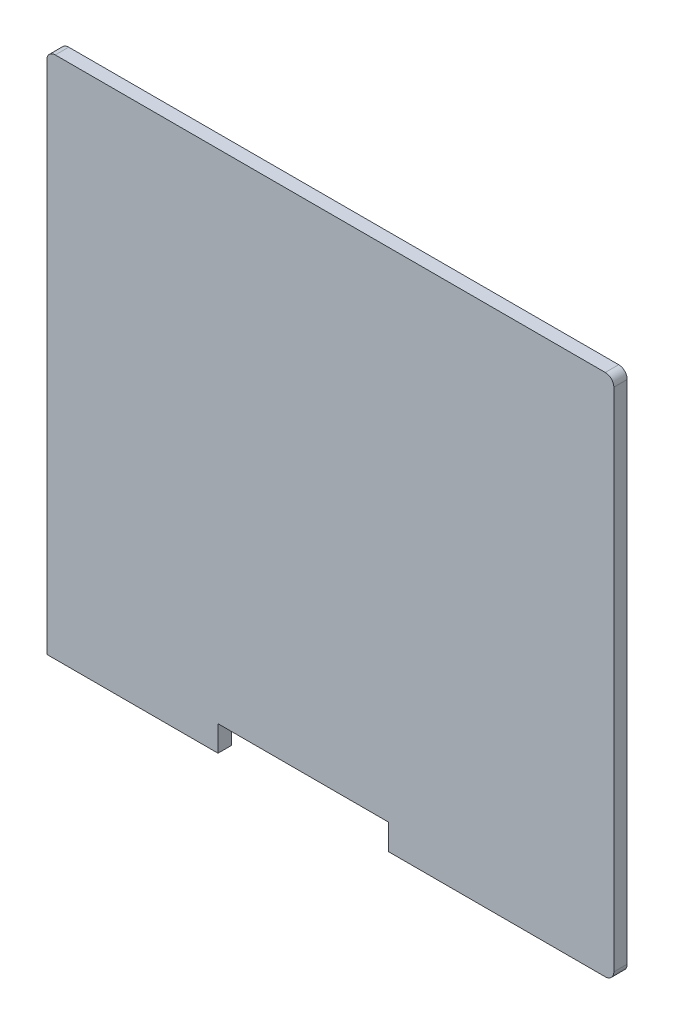
SolidWorks part; units mm, degrees
ref_plane "Front Plane" through (0, 0, 0) normal (0, 0, 1) x (1, 0, 0)
ref_plane "Top Plane" through (0, 0, 0) normal (0, 1, 0) x (1, 0, 0)
ref_plane "Right Plane" through (0, 0, 0) normal (1, 0, 0) x (0, 0, -1)
sketch "BPR2 PCB Outline" plane through (0, 0, 0) normal (0, 0, 1) x (1, 0, 0)
  line L0 (75.643, 7.3176) -> (75.643, 10.3176)
  line L1 (56.571, 68.6726) -> (121.041, 68.6726)
  line L2 (55.571, 67.6726) -> (55.571, 7.3176)
  line L3 (55.571, 7.3176) -> (75.643, 7.3176)
  line L4 (122.041, 67.6726) -> (122.041, 8.3176)
  line L5 (75.643, 10.3176) -> (95.643, 10.3176)
  line L6 (95.643, 10.3176) -> (95.643, 7.3176)
  line L7 (95.643, 7.3176) -> (121.041, 7.3176)
  arc A0 (121.041, 7.3176) -> (122.041, 8.3176) centre (121.041, 8.3176) ccw
  arc A1 (121.041, 68.6726) -> (122.041, 67.6726) centre (121.041, 67.6726) cw
  arc A2 (56.571, 68.6726) -> (55.571, 67.6726) centre (56.571, 67.6726) ccw
  point P6 (122.041, 7.3176)
  point P9 (122.041, 68.6726)
  point P12 (55.571, 68.6726)
  dimension "D4" = 25.398
  dimension "D3" = 1
  dimension "D1" = 61.355
  dimension "D5" = 20
  dimension "D6" = 3
sketch "23" plane through (0, 0, 0) normal (0, 0, 1) x (1, 0, 0)
  point P0 (0, 0)
extrude "Boss-Extrude1" add sketch "BPR2 PCB Outline" against normal blind 1.5748
